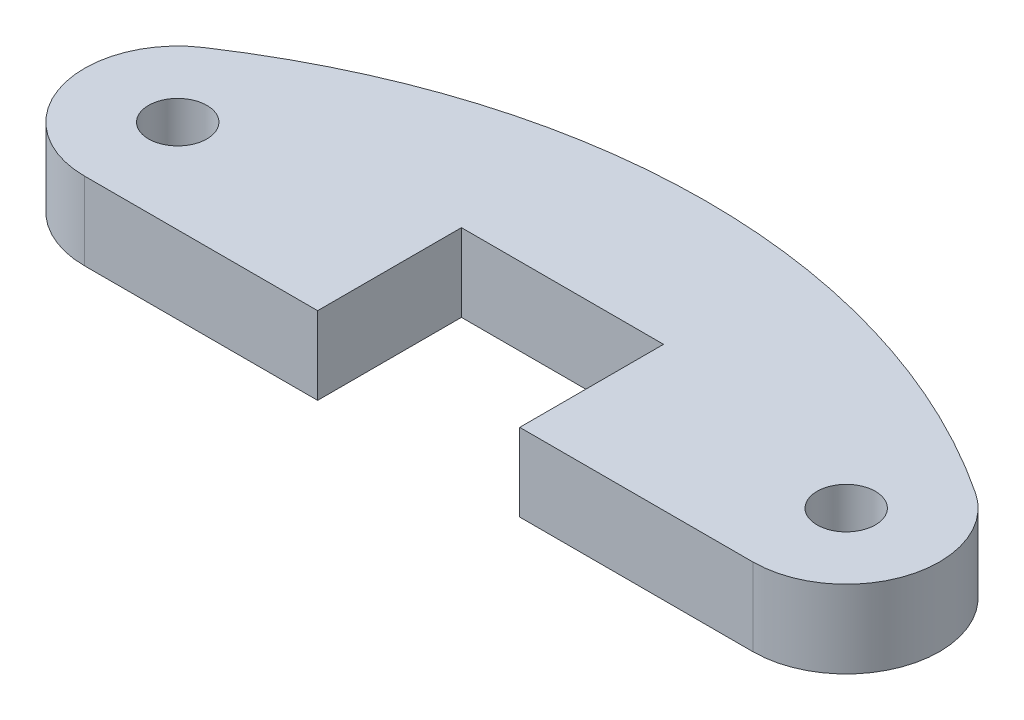
SolidWorks part; units mm, degrees
ref_plane "Front Plane" through (0, 0, 0) normal (0, 0, 1) x (1, 0, 0)
ref_plane "Top Plane" through (0, 0, 0) normal (0, 1, 0) x (1, 0, 0)
ref_plane "Right Plane" through (0, 0, 0) normal (1, 0, 0) x (0, 0, -1)
sketch "Sketch1" plane through (0, 0, 0) normal (0, 1, 0) x (1, 0, 0)
  line L0 (21.5, 0) -> (-21.5, 0) construction
  line L1 (21.5, -6) -> (6.5, -6)
  line L3 (0, -55) -> (0, 55) construction
  line L5 (6.5, -3.25) -> (6.5, 3.25)
  line L6 (6.5, 3.25) -> (-6.5, 3.25)
  line L7 (-6.5, -3.25) -> (-6.5, 3.25)
  line L8 (6.5, -3.25) -> (-6.5, 3.25) construction
  line L9 (6.5, 3.25) -> (-6.5, -3.25) construction
  line L10 (-6.5, -3.25) -> (-6.5, -6)
  line L11 (6.5, -3.25) -> (6.5, -6)
  line L12 (-6.5, -6) -> (-21.5, -6)
  arc A0 (21.5, -6) -> (24.8166, 5) centre (21.5, 0) ccw
  arc A1 (-24.8166, 5) -> (-21.5, -6) centre (-21.5, 0) ccw
  circle A2 centre (-21.5, 0) radius 1.875
  circle A3 centre (21.5, 0) radius 1.875
  spline S0 degree 3 poles (-24.8166, 5) (-8.7363, 15.6665) (10.3786, 14.5771) (24.8166, 5) knots 0 0 0 0 1 1 1 1
  point P2 (0, 0)
  point P8 (0, 0)
  dimension "D5" = 3.75
  dimension "D2" = 6.5
  dimension "D3" = 43
  dimension "D4" = 13
  dimension "D6" = 5
extrude "Boss-Extrude1" add sketch "Sketch1" along normal blind 5
